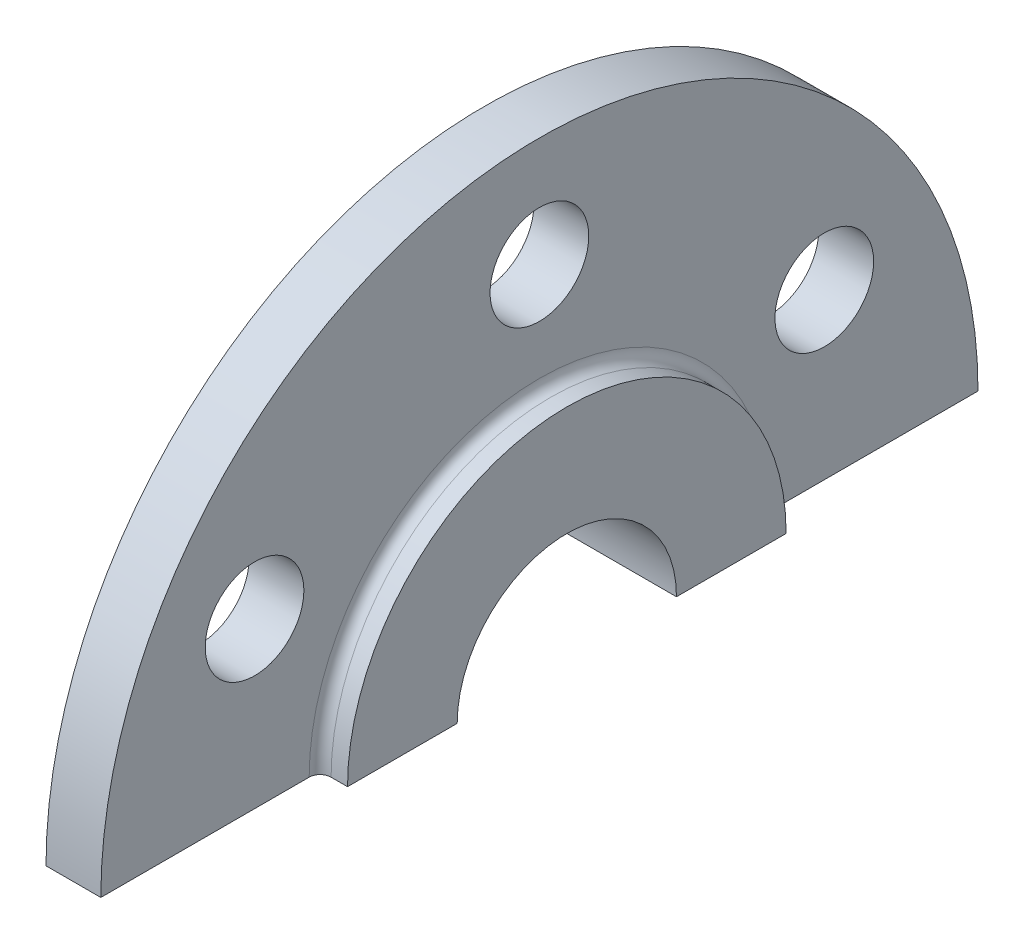
SolidWorks part; units mm, degrees
ref_plane "Front Plane" through (0, 0, 0) normal (0, 0, 1) x (1, 0, 0)
ref_plane "Top Plane" through (0, 0, 0) normal (0, 1, 0) x (1, 0, 0)
ref_plane "Right Plane" through (0, 0, 0) normal (1, 0, 0) x (0, 0, -1)
sketch "Sketch2" plane through (0, 0, 0) normal (0, 1, 0) x (1, 0, 0)
  line L0 (0, 20) -> (0, 80)
  line L1 (0, 80) -> (5, 80)
  line L2 (5, 80) -> (5, 40)
  line L3 (5, 40) -> (10, 40)
  line L4 (10, 40) -> (10, 20)
  line L5 (10, 20) -> (0, 20)
  line L6 (0, 20) -> (-10, 20)
  line L7 (-10, 20) -> (-10, 40)
  line L8 (-10, 40) -> (-5, 40)
  line L9 (-5, 40) -> (-5, 80)
  line L10 (-5, 80) -> (0, 80)
  dimension "D1" = 20
  dimension "D2" = 5
  dimension "D3" = 5
  dimension "D4" = 60
  dimension "D5" = 20
  dimension "D6" = 5
  dimension "D7" = 5
ref_axis "Axis1" through (-0.5, 0, 0) along (1, 0, 0)
revolve "Revolve1" add sketch "Sketch2" angle 180 about axis through (-0.5, 0, 0) along (1, 0, 0)
sketch "Sketch3" plane through (0, 0, 0) normal (1, 0, 0) x (0, 0, -1)
  line L0 (0, 0) -> (51.9615, 30) construction
  line L1 (0, 0) -> (0, 60) construction
  line L2 (0, 0) -> (-51.9615, 30) construction
  circle A0 centre (-51.9615, 30) radius 9
  circle A1 centre (0, 60) radius 9
  circle A2 centre (51.9615, 30) radius 9
  circle A3 centre (0, 0) radius 60 construction
  dimension "D1" = 18
  dimension "D2" = 120
  dimension "D3" = 60
  dimension "D4" = 60
extrude "Cut-Extrude1" cut sketch "Sketch3" against normal through all both and the other way through all
fillet "Fillet1" radius 2 2 edges at (-5, 40, 0) (5, 40, 0)
